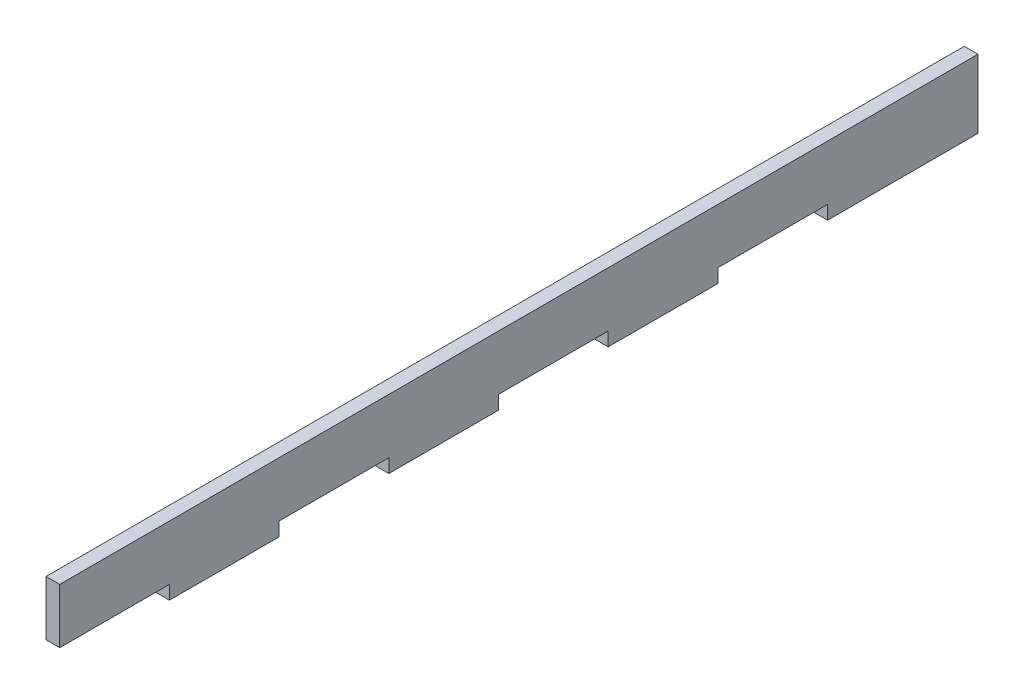
SolidWorks part; units mm, degrees
ref_plane "Front Plane" through (0, 0, 0) normal (0, 0, 1) x (1, 0, 0)
ref_plane "Top Plane" through (0, 0, 0) normal (0, 1, 0) x (1, 0, 0)
ref_plane "Right Plane" through (0, 0, 0) normal (1, 0, 0) x (0, 0, -1)
sketch "Sketch2" plane through (0, 0, 0) normal (1, 0, 0) x (0, 0, -1)
  line L30 (48.3194, 0) -> (99.1194, 0)
  line L31 (-2.4806, 6.35) -> (-2.4806, 31.75)
  line L32 (-2.4806, 31.75) -> (422.7895, 31.75)
  line L33 (422.7895, 0) -> (422.7895, 31.75)
  line L34 (353.1194, 6.35) -> (353.1194, 0) construction
  line L35 (302.3194, 6.35) -> (353.1194, 6.35) construction
  line L36 (302.3194, 6.35) -> (302.3194, 0) construction
  line L37 (251.5194, 6.35) -> (251.5194, 0) construction
  line L38 (200.7194, 6.35) -> (251.5194, 6.35) construction
  line L39 (200.7194, 6.35) -> (200.7194, 0) construction
  line L40 (149.9194, 6.35) -> (149.9194, 0) construction
  line L41 (99.1194, 6.35) -> (149.9194, 6.35) construction
  line L42 (99.1194, 6.35) -> (99.1194, 0) construction
  line L43 (48.3194, 6.35) -> (48.3194, 0) construction
  line L44 (-2.4806, 6.35) -> (48.3194, 6.35) construction
  line L45 (422.7895, 31.75) -> (422.7895, 35.3357) construction
  line L46 (353.1194, 6.35) -> (353.1194, 0)
  line L47 (302.3194, 6.35) -> (353.1194, 6.35)
  line L48 (302.3194, 6.35) -> (302.3194, 0)
  line L49 (251.5194, 6.35) -> (251.5194, 0)
  line L50 (200.7194, 6.35) -> (251.5194, 6.35)
  line L51 (200.7194, 6.35) -> (200.7194, 0)
  line L52 (149.9194, 6.35) -> (149.9194, 0)
  line L53 (99.1194, 6.35) -> (149.9194, 6.35)
  line L54 (99.1194, 6.35) -> (99.1194, 0)
  line L55 (48.3194, 6.35) -> (48.3194, 0)
  line L56 (-2.4806, 6.35) -> (48.3194, 6.35)
  line L57 (353.1194, 0) -> (422.7895, 0)
  line L58 (251.5194, 0) -> (302.3194, 0)
  line L59 (149.9194, 0) -> (200.7194, 0)
extrude "Boss-Extrude1" add sketch "Sketch2" along normal blind 6.35
